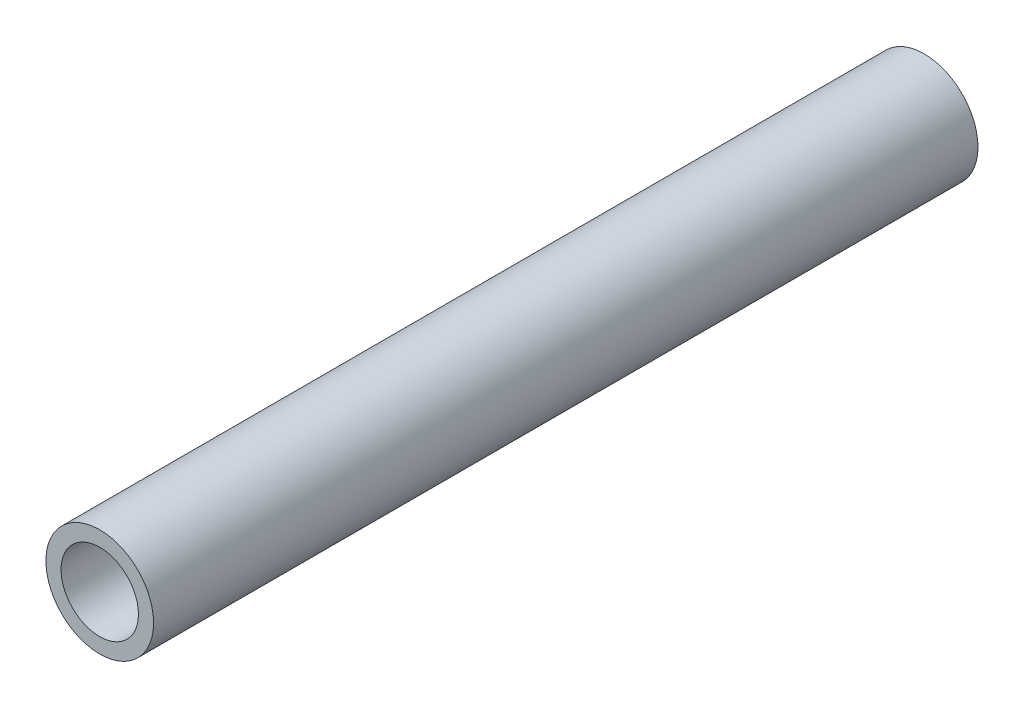
SolidWorks part; units mm, degrees
material "Acciaio inossidabile fuso"
ref_plane "Piano frontale" through (0, 0, 0) normal (0, 0, 1) x (1, 0, 0)
ref_plane "Piano superiore" through (0, 0, 0) normal (0, 1, 0) x (1, 0, 0)
ref_plane "Piano destro" through (0, 0, 0) normal (1, 0, 0) x (0, 0, -1)
sketch "Schizzo1" plane through (0, 0, 0) normal (0, 0, 1) x (1, 0, 0)
  circle A0 centre (0, 0) radius 3.2
  dimension "D1" = 6.4
extrude "Estrusione-Sottile1" add sketch "Schizzo1" along normal blind 49 thin thin type one direction reverse wall 0.9
